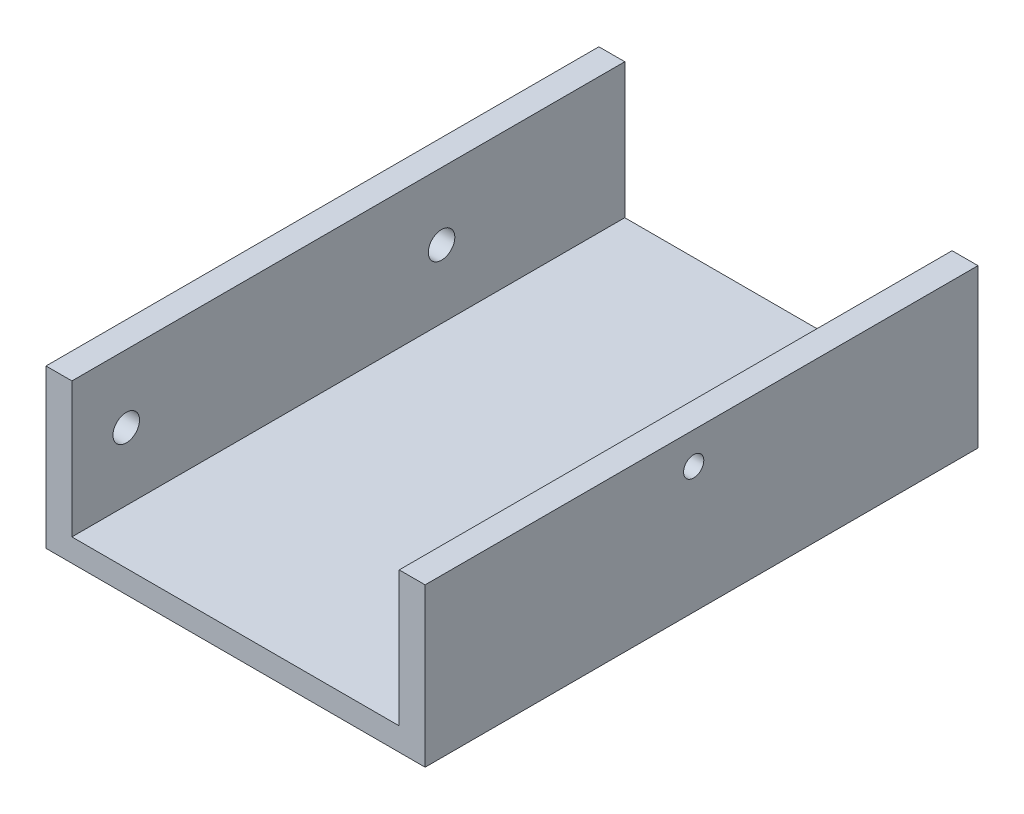
SolidWorks part; units mm, degrees
material "6061 Alloy"
ref_plane "Front Plane" through (0, 0, 0) normal (0, 0, 1) x (1, 0, 0)
ref_plane "Top Plane" through (0, 0, 0) normal (0, 1, 0) x (1, 0, 0)
ref_plane "Right Plane" through (0, 0, 0) normal (1, 0, 0) x (0, 0, -1)
sketch "Sketch2" plane through (0, 0, 0) normal (0, 0, 1) x (1, 0, 0)
  line L0 (-38.1, 0) -> (38.1, 0)
  line L1 (-38.1, 0) -> (-38.1, 31.75)
  line L2 (-38.1, 31.75) -> (-32.893, 31.75)
  line L3 (-32.893, 31.75) -> (-32.893, 4.5974)
  line L4 (-32.893, 4.5974) -> (32.893, 4.5974)
  line L5 (32.893, 4.5974) -> (32.893, 31.75)
  line L6 (32.893, 31.75) -> (38.1, 31.75)
  line L7 (38.1, 31.75) -> (38.1, 0)
  point P8 (0, 4.5974)
  point P10 (0, 0)
  point P11 (35.4965, 31.75)
  dimension "D1" = 5.207
  dimension "D2" = 31.75
  dimension "D3" = 76.2
  dimension "D4" = 31.75
extrude "Boss-Extrude3" add sketch "Sketch2" along normal blind 111.125
sketch "Sketch4" plane through (-32.893, 0, 0) normal (1, 0, 0) x (0, 0, -1)
  line L0 (0, 4.5974) -> (0, 31.75) construction
  line L1 (-111.125, 31.75) -> (0, 31.75) construction
  circle A0 centre (-36.83, 18.288) radius 2.667
  dimension "D1" = 36.83
  dimension "D2" = 5.334
  dimension "D3" = 13.462
extrude "Cut-Extrude1" cut sketch "Sketch4" against normal through all
sketch "Sketch5" plane through (-32.893, 0, 0) normal (1, 0, 0) x (0, 0, -1)
  line L1 (-111.125, 4.5974) -> (-111.125, 31.75) construction
  circle A0 centre (-100.203, 18.1634) radius 2.667
  dimension "D1" = 10.922
  dimension "D2" = 5.334
extrude "Cut-Extrude2" cut sketch "Sketch5" against normal through all
sketch "Sketch6" plane through (32.893, 0, 0) normal (-1, 0, 0) x (0, 0, 1)
  line L0 (111.125, 31.75) -> (111.125, 4.5974) construction
  line L1 (111.125, 31.75) -> (0, 31.75) construction
  circle A0 centre (57.15, 25.4) radius 2.032
  dimension "D1" = 53.975
  dimension "D2" = 6.35
  dimension "D3" = 4.064
extrude "Cut-Extrude3" cut sketch "Sketch6" against normal through all
